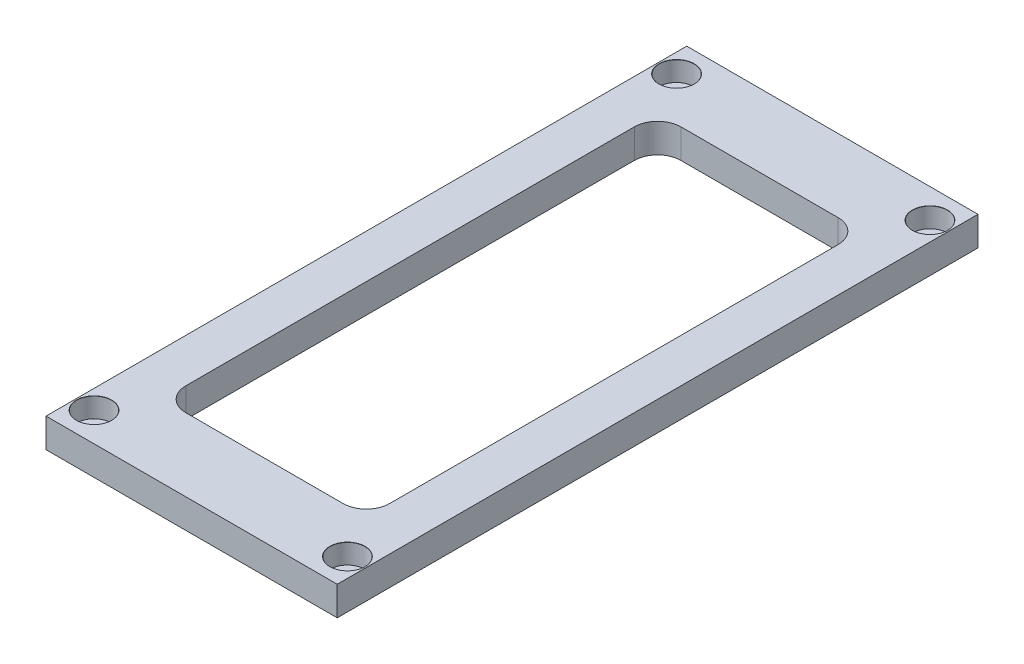
SolidWorks part; units mm, degrees
material "6061 Alloy"
ref_plane "Front Plane" through (0, 0, 0) normal (0, 0, 1) x (1, 0, 0)
ref_plane "Top Plane" through (0, 0, 0) normal (0, 1, 0) x (1, 0, 0)
ref_plane "Right Plane" through (0, 0, 0) normal (1, 0, 0) x (0, 0, -1)
sketch "Sketch1" plane through (0, 0, 0) normal (0, 1, 0) x (1, 0, 0)
  line L1 (25, -55) -> (-25, -55)
  line L2 (25, -55) -> (25, 55)
  line L3 (25, 55) -> (-25, 55)
  line L4 (-25, -55) -> (-25, 55)
  line L5 (25, -55) -> (-25, 55) construction
  line L6 (25, 55) -> (-25, -55) construction
  point P0 (0, 0)
  dimension "D1" = 110
  dimension "D2" = 50
extrude "Boss-Extrude1" add sketch "Sketch1" along normal blind 5
sketch "Sketch2" plane through (0, 5, 0) normal (0, 1, 0) x (1, 0, 0)
  line L0 (0, -2.75) -> (0, 2.75) construction
  line L1 (-2.75, 0) -> (2.75, 0) construction
  line L2 (-25, 55) -> (-25, -55) construction
  point P0 (-21.75, 50)
  point P3 (21.75, 50)
  point P6 (21.75, -50)
  point P7 (-21.75, -50)
  dimension "D1" = 3.25
  dimension "D2" = 100
hole_wizard "CBORE for M3 Hexagon socket head cap screws1" positions "3DSketch2" profile "Sketch4" counterbore size "M3" standard "GB"
sketch3d "3DSketch2"
  point P0 (-21.75, 5, -50)
  point P3 (21.75, 5, -50)
  point P6 (-21.75, 5, 50)
  point P9 (21.75, 5, 50)
sketch "Sketch4" plane through (-21.75, 5, -50) normal (1, 0, 0) x (0, 0, 1)
  line L0 (0, 0) -> (0, 10.9614)
  line L1 (0, 10.9614) -> (1.6, 10)
  line L2 (1.6, 10) -> (1.6, 3.4)
  line L3 (1.6, 3.4) -> (3, 3.4)
  line L5 (3, 3.4) -> (3, 0.025)
  line L6 (3, 0.025) -> (3.025, 0)
  line L7 (3.025, 0) -> (0, 0)
  line L8 (-3, 0.025) -> (-3.025, 0) construction
  line L10 (0, 10.9614) -> (-1.6, 10) construction
  line L11 (0, -6.35) -> (0, 107.95) construction
  dimension "Hole Dia." = 3.2
  dimension "Hole Depth" = 10
  dimension "C'Bore Dia." = 6
  dimension "C'Bore Depth" = 3.4
  dimension "Near C'Sink Dia." = 6.05
  dimension "Near C'Sink Angle" = 90
  dimension "Drill Angle" = 118
sketch "Sketch5" plane through (0, 5, 0) normal (0, 1, 0) x (1, 0, 0)
  line L1 (17.5, -42.5) -> (-17.5, -42.5)
  line L2 (17.5, -42.5) -> (17.5, 42.5)
  line L3 (17.5, 42.5) -> (-17.5, 42.5)
  line L4 (-17.5, -42.5) -> (-17.5, 42.5)
  line L5 (17.5, -42.5) -> (-17.5, 42.5) construction
  line L6 (17.5, 42.5) -> (-17.5, -42.5) construction
  point P0 (0, 0)
  dimension "D1" = 35
  dimension "D2" = 85
extrude "Cut-Extrude1" cut sketch "Sketch5" against normal through all
fillet "Fillet1" radius 4 4 edges at (17.5, 2.5, -42.5) (17.5, 2.5, 42.5) (-17.5, 2.5, 42.5) (-17.5, 2.5, -42.5)
